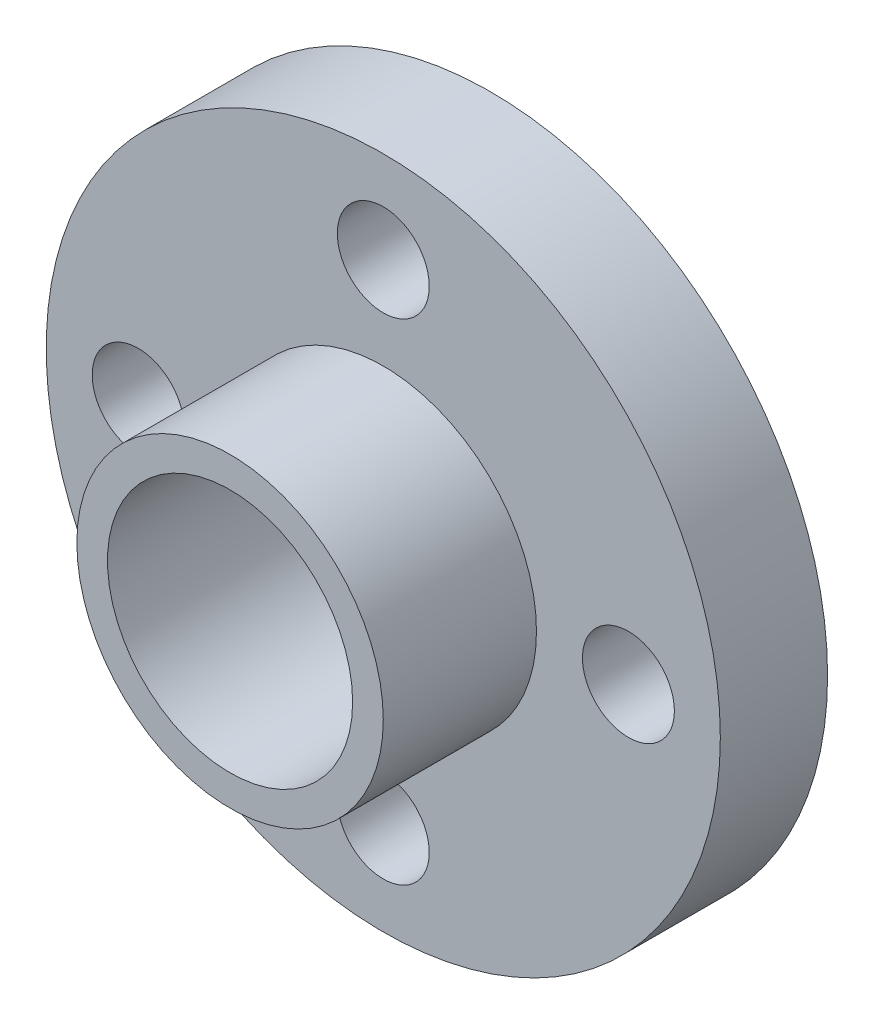
SolidWorks part; units mm, degrees
ref_plane "前视基准面" through (0, 0, 0) normal (0, 0, 1) x (1, 0, 0)
ref_plane "上视基准面" through (0, 0, 0) normal (0, 1, 0) x (1, 0, 0)
ref_plane "右视基准面" through (0, 0, 0) normal (1, 0, 0) x (0, 0, -1)
sketch "草图1" plane through (0, 0, 0) normal (0, 0, 1) x (1, 0, 0)
  circle A0 centre (0, 0) radius 5
extrude "凸台-拉伸1" add sketch "草图1" along normal blind 2
sketch "草图2" plane through (0, 0, 2) normal (0, 0, 1) x (1, 0, 0)
  circle A0 centre (0, 0) radius 11
extrude "凸台-拉伸2" add sketch "草图2" along normal blind 3.5 contours A0
sketch "草图4" plane through (0, 0, 5.5) normal (0, 0, 1) x (1, 0, 0)
  circle A0 centre (0, 0) radius 5
extrude "凸台-拉伸3" add sketch "草图4" along normal blind 5
sketch "草图5" plane through (0, 0, 5.5) normal (0, 0, 1) x (1, 0, 0)
  circle A0 centre (0, 8) radius 1.5
  circle A1 centre (8, 0) radius 1.5
  circle A2 centre (0, -8) radius 1.5
  circle A3 centre (-8, 0) radius 1.5
  dimension "D1" = 4
extrude "切除-拉伸2" cut sketch "草图5" against normal blind 5
sketch "草图6" plane through (0, 0, 10.5) normal (0, 0, 1) x (1, 0, 0)
  circle A0 centre (0, 0) radius 4
extrude "切除-拉伸3" cut sketch "草图6" against normal through all
